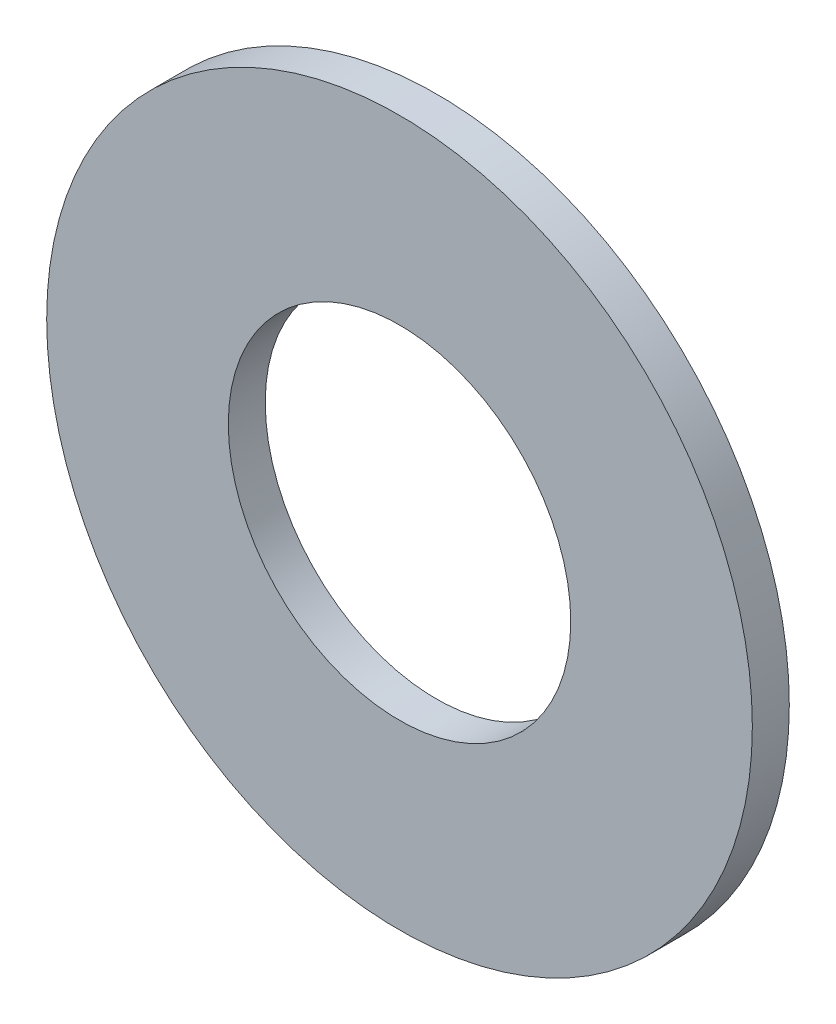
SolidWorks part; units mm, degrees
ref_plane "Front Plane" through (0, 0, 0) normal (0, 0, 1) x (1, 0, 0)
ref_plane "Top Plane" through (0, 0, 0) normal (0, 1, 0) x (1, 0, 0)
ref_plane "Right Plane" through (0, 0, 0) normal (1, 0, 0) x (0, 0, -1)
sketch "Sketch1" plane through (0, 0, 0) normal (0, 0, 1) x (1, 0, 0)
  circle A0 centre (0, 0) radius 34
  circle A1 centre (0, 0) radius 16.5
  dimension "D1" = 68
  dimension "D2" = 33
extrude "Boss-Extrude1" add sketch "Sketch1" along normal blind 3.562
